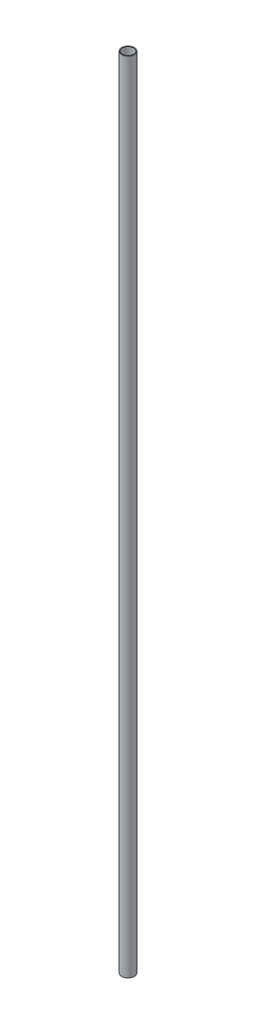
SolidWorks part; units mm, degrees
material "Manual Density from Real Component Tube REAR"
ref_plane "Piano frontale" through (0, 0, 0) normal (0, 0, 1) x (1, 0, 0)
ref_plane "Piano superiore" through (0, 0, 0) normal (0, 1, 0) x (1, 0, 0)
ref_plane "Piano destro" through (0, 0, 0) normal (1, 0, 0) x (0, 0, -1)
sketch "Schizzo1" plane through (0, 0, 0) normal (0, 1, 0) x (1, 0, 0)
  circle A0 centre (0, 0) radius 9
  circle A1 centre (0, 0) radius 8
  dimension "D1" = 18
  dimension "D2" = 16
extrude "Estrusione-Estrusione1" add sketch "Schizzo1" along normal blind 1150
ref_plane "PianoTangenteSuperiore" through (0, 0, -9) normal (0, 0, -1) x (-1, 0, 0)
